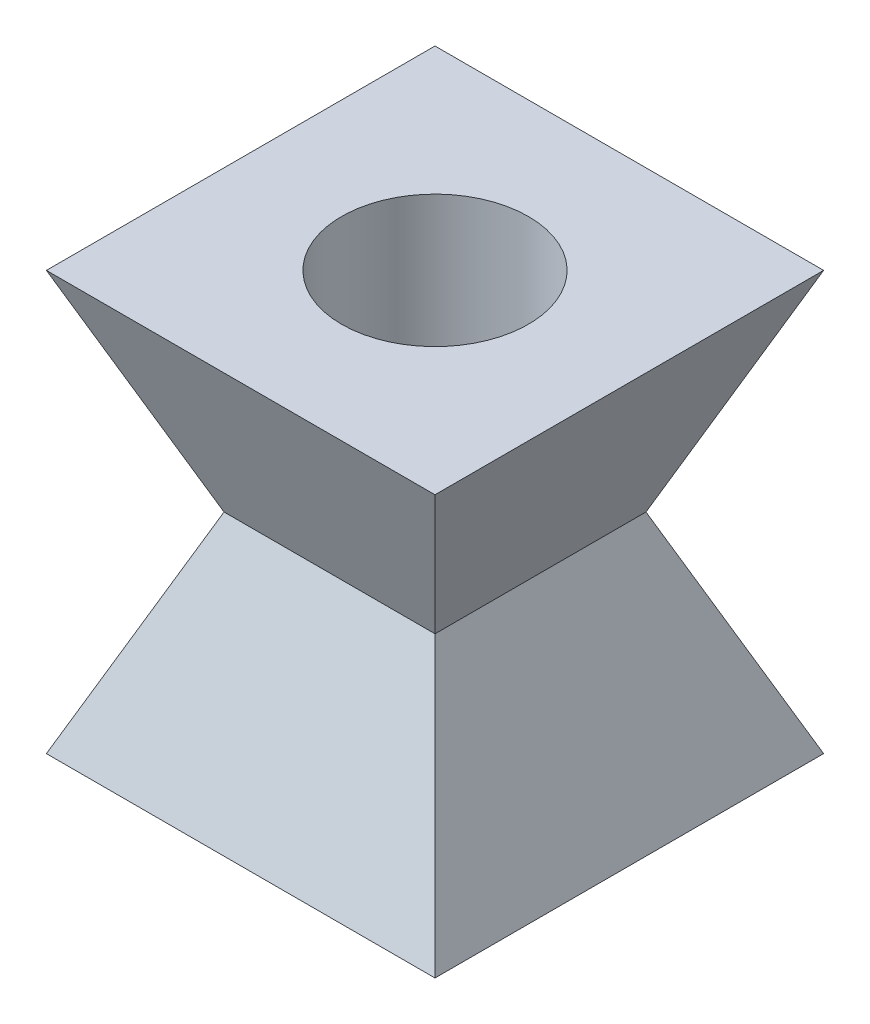
SolidWorks part; units mm, degrees
material "Acier inoxydable moulé"
ref_plane "Plan de face" through (0, 0, 0) normal (0, 0, 1) x (1, 0, 0)
ref_plane "Plan de dessus" through (0, 0, 0) normal (0, 1, 0) x (1, 0, 0)
ref_plane "Plan de droite" through (0, 0, 0) normal (1, 0, 0) x (0, 0, -1)
sketch "Esquisse2" plane through (0, 0, 0) normal (0, 0, 1) x (1, 0, 0)
  line L0 (-28.2294, 0) -> (28.2294, 0)
  line L1 (55, 0) -> (-55, 0) construction
  line L2 (28.2294, 0) -> (52, 56)
  line L3 (52, 56) -> (-52, 56)
  line L4 (0, -55) -> (0, 55) construction
  line L5 (-28.2294, 0) -> (-52, 56)
  line L6 (-52, 56) -> (-52, -12.4684) construction
  line L7 (-28.2294, 0) -> (-52, -56)
  line L8 (52, -56) -> (-52, -56)
  line L9 (28.2294, 0) -> (52, -56)
  point P10 (0, 56)
  point P11 (0, 0)
  point P14 (0, -56)
  dimension "D1" = 104
  dimension "D2" = 56
  dimension "D3" = 23
extrude "Boss.-Extru.2" add sketch "Esquisse2" along normal mid plane 104 contours L9 L0 L7 L8 | L5 L0 L2 L3
sketch "Esquisse3" plane through (0, 56, 0) normal (0, 1, 0) x (1, 0, 0)
  circle A0 centre (0, 0) radius 25
extrude "Enlèv. mat.-Extru.1" cut sketch "Esquisse3" against normal through all
sketch "Esquisse4" plane through (0, 0, 0) normal (1, 0, 0) x (0, 0, -1)
  line L0 (-52, 56) -> (-52, 1.2826)
  line L1 (-52, 56) -> (52, 56) construction
  line L2 (-52, 0) -> (-52, 56) construction
  line L3 (-52, 56) -> (-28.2294, 0)
  line L4 (55, 0) -> (-55, 0) construction
  line L5 (-28.2294, 0) -> (-52, -56)
  line L6 (0, 55) -> (0, -55) construction
  line L7 (28.2294, 0) -> (52, -56)
  line L8 (52, 56) -> (28.2294, 0)
  line L9 (52, 56) -> (52, -56)
  line L10 (-52, 56) -> (-52, -56)
  dimension "D1" = 23
extrude "Enlèv. mat.-Extru.2" cut sketch "Esquisse4" against normal through all both and the other way through all contours L0 L10 L5 L3 | L8 L7 L9
equation "\"A\" = 112"
equation "\"B\" = 104"
equation "\"C\" = 23"
equation "\"D1@Esquisse2\"=\"B\""
equation "\"D3@Esquisse2\"=\"C\""
equation "\"D1@Boss.-Extru.2\"=\"B\""
equation "\"D1@Esquisse4\"=\"C\""
equation "\"A/2\"= \"A\" / 2"
equation "\"D2@Esquisse2\"=\"A/2\""
